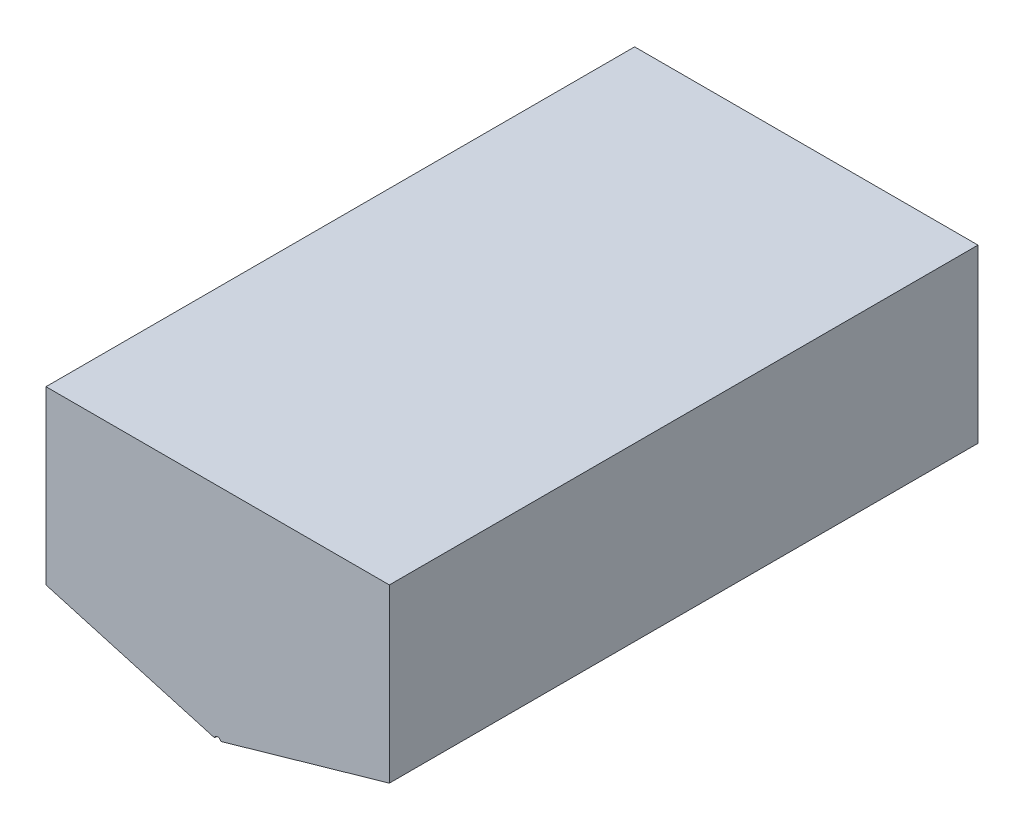
SolidWorks part; units mm, degrees
ref_plane "Plano frontal" through (0, 0, 0) normal (0, 0, 1) x (1, 0, 0)
ref_plane "Plano superior" through (0, 0, 0) normal (0, 1, 0) x (1, 0, 0)
ref_plane "Plano direito" through (0, 0, 0) normal (1, 0, 0) x (0, 0, -1)
sketch "Esboço1" plane through (0, 0, 0) normal (0, 0, 1) x (1, 0, 0)
  line L2 (35, -12.5) -> (35, 22.5)
  line L3 (35, 22.5) -> (-35, 22.5)
  line L4 (-35, -12.5) -> (-35, 22.5)
  line L5 (24.2308, -15.5769) -> (-35, 22.5) construction
  line L6 (35, 22.5) -> (-24.2308, -15.5769) construction
  line L7 (-0.3846, -22.3901) -> (-35, -12.5)
  line L8 (0.4289, -22.3775) -> (35, -12.5)
  arc A0 (0.4289, -22.3775) -> (-0.3846, -22.3901) centre (0.024, -22.5069) ccw
  point P0 (0, 0)
  point P2 (35, -22.5)
  point P4 (-35, -22.5)
  dimension "D2" = 0.85
  dimension "D3" = 0.425
  dimension "D1" = 70
extrude "Ressalto-extrusão1" add sketch "Esboço1" along normal blind 120
sketch "Esboço3" plane through (0, 0, 120) normal (0, 0, 1) x (1, 0, 0)
  circle A1 centre (0, -22.5) radius 0.675
extrude "Corte-extrusão1" cut sketch "Esboço3" against normal blind 30
